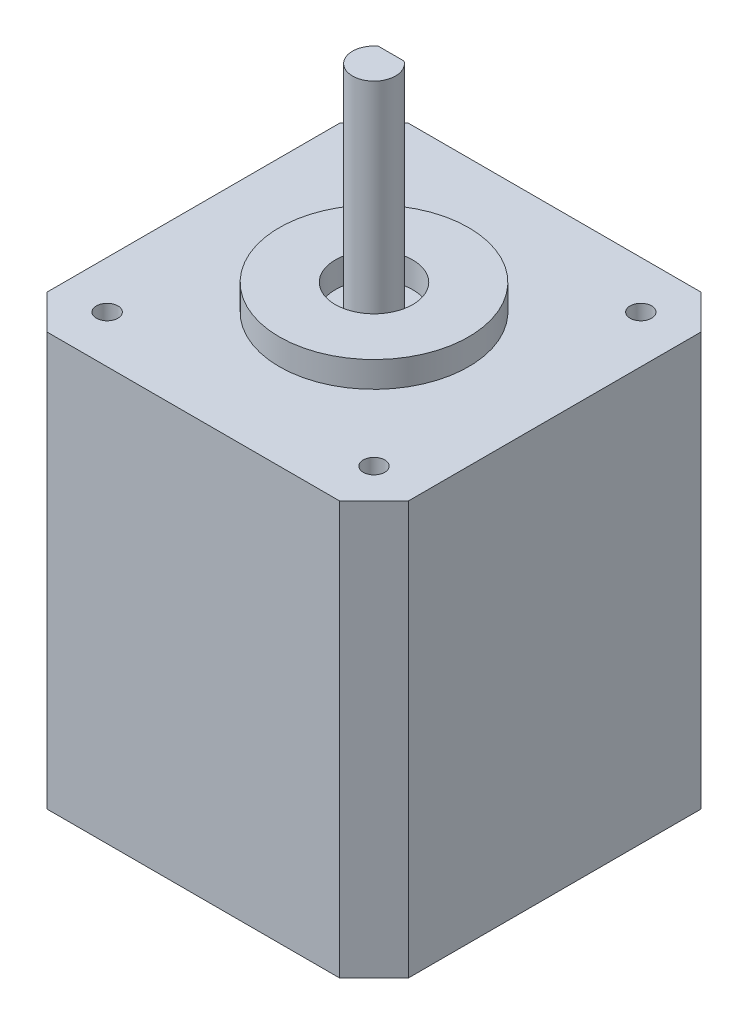
SolidWorks part; units mm, degrees
ref_plane "Alzado" through (0, 0, 0) normal (0, 0, 1) x (1, 0, 0)
ref_plane "Planta" through (0, 0, 0) normal (0, 1, 0) x (1, 0, 0)
ref_plane "Vista lateral" through (0, 0, 0) normal (1, 0, 0) x (0, 0, -1)
sketch "Croquis1" plane through (0, 0, 0) normal (0, 1, 0) x (1, 0, 0)
  line L1 (21, -21) -> (-21, -21)
  line L2 (21, -21) -> (21, 21)
  line L3 (21, 21) -> (-21, 21)
  line L4 (-21, -21) -> (-21, 21)
  line L5 (21, -21) -> (-21, 21) construction
  line L6 (21, 21) -> (-21, -21) construction
  point P0 (0, 0)
  dimension "D1" = 42
extrude "Saliente-Extruir1" add sketch "Croquis1" along normal blind 48
sketch "Croquis2" plane through (0, 48, 0) normal (0, 1, 0) x (1, 0, 0)
  circle A0 centre (0, 0) radius 11
  circle A1 centre (0, 0) radius 4.5
  dimension "D1" = 22
  dimension "D2" = 9
extrude "Saliente-Extruir2" add sketch "Croquis2" along normal blind 3
sketch "Croquis3" plane through (0, 48, 0) normal (0, 1, 0) x (1, 0, 0)
  line L0 (1.5, 2) -> (-1.5, 2)
  arc A0 (-1.5, 2) -> (1.5, 2) centre (0, 0) ccw
  dimension "D1" = 5
  dimension "D2" = 3
extrude "Saliente-Extruir3" add sketch "Croquis3" along normal blind 25
hole_wizard "Taladro roscado M31" positions "Croquis4" profile "Croquis6" tap size "M3" standard "ISO"
sketch "Croquis4" plane through (0, 48, 0) normal (0, 1, 0) x (1, 0, 0)
  line L0 (15.5, 15.5) -> (-15.5, -15.5) construction
  point P0 (-15.5, 15.5)
  point P2 (-15.5, -15.5)
  point P4 (15.5, -15.5)
  point P6 (15.5, 15.5)
  point P16 (0, 0)
  point P18 (18.0994, -15.2679)
  point P19 (0, 0)
  point P20 (0, 0)
  dimension "D1" = 31
  dimension "D2" = 31
sketch "Croquis6" plane through (-15.5, 48, -15.5) normal (1, 0, 0) x (0, 0, 1)
  line L0 (0, 0) -> (0, 9.2511)
  line L1 (0, 9.2511) -> (1.25, 8.5)
  line L2 (1.25, 8.5) -> (1.25, 0)
  line L5 (1.25, 0) -> (0, 0)
  line L10 (0, 9.2511) -> (-1.25, 8.5) construction
  line L11 (0, -6.35) -> (0, 107.95) construction
  dimension "Diámetro de perforador para roscar" = 2.5
  dimension "Profundidad de perforador para roscar" = 8.5
  dimension "Ángulo de perforador" = 118
cosmetic thread "Rosca de taladro1" parameters "D1"=6, "D2"=3
cosmetic thread "Rosca de taladro2" parameters "D1"=6, "D2"=3
cosmetic thread "Rosca de taladro3" parameters "D1"=6, "D2"=3
cosmetic thread "Rosca de taladro4" parameters "D1"=6, "D2"=3
chamfer "Chaflán1" distance 4 angle 45 4 edges at (21, 24, -21) (21, 24, 21) (-21, 24, 21) (-21, 24, -21)
